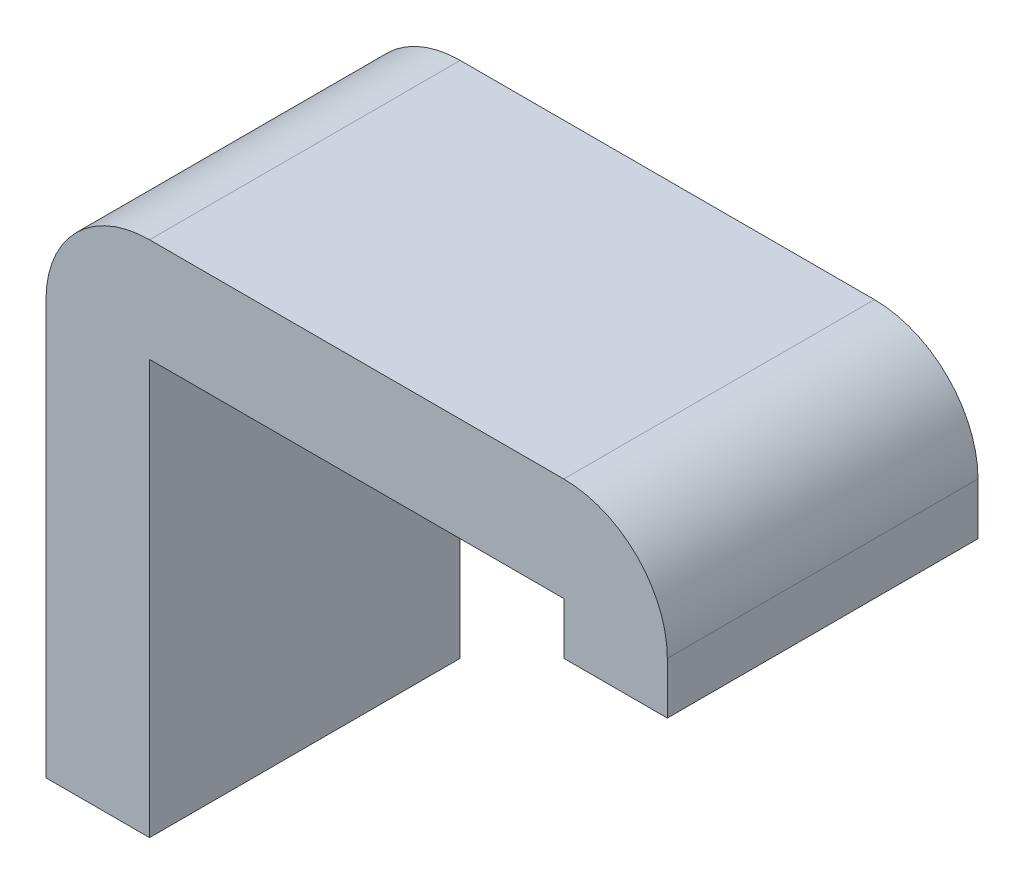
SolidWorks part; units mm, degrees
ref_plane "Plan de face" through (0, 0, 0) normal (0, 0, 1) x (1, 0, 0)
ref_plane "Plan de dessus" through (0, 0, 0) normal (0, 1, 0) x (1, 0, 0)
ref_plane "Plan de droite" through (0, 0, 0) normal (1, 0, 0) x (0, 0, -1)
sketch "Esquisse2" plane through (0, 0, 0) normal (0, 0, 1) x (1, 0, 0)
  line L0 (-35, 0) -> (35, 0)
  line L1 (35, 0) -> (35, -50)
  line L3 (-35, 0) -> (-35, -50)
  point P0 (0, 0)
  point P4 (0, 0)
  dimension "D1" = 50
  dimension "D2" = 70
  dimension "D3" = 50
sketch "Esquisse5" plane through (0, 0, 0) normal (0, 0, 1) x (1, 0, 0)
  line L0 (-20, 0) -> (20, 0)
  line L1 (-30, -10) -> (-30, -50)
  line L4 (30, -10) -> (30, -15)
  arc A0 (20, 0) -> (30, -10) centre (20, -10) cw
  arc A1 (-20, 0) -> (-30, -10) centre (-20, -10) ccw
  point P4 (0, 0)
  point P8 (30, 0)
  point P11 (-30, 0)
  point P12 (0, 0)
  point P13 (0, 0)
  dimension "D4" = 10
  dimension "D1" = 50
  dimension "D2" = 60
  dimension "D3" = 15
sketch "Esquisse7" plane through (0, 0, 0) normal (0, 1, 0) x (1, 0, 0)
  circle A0 centre (-20.3431, 18.4803) radius 44.0109
extrude "Extru.-Mince3" add sketch "Esquisse5" along normal blind 30 thin contours L4 A0 L0 A1 L1
sketch "Esquisse9" plane through (0, -50, 0) normal (0, -1, 0) x (1, 0, 0)
  line L0 (-28.3266, 28.158) -> (-21.9398, 28.158)
  line L1 (-21.9398, 28.158) -> (-21.9398, 2.3151)
  line L2 (-21.9398, 2.3151) -> (-28.3266, 2.3151)
  line L3 (-28.3266, 2.3151) -> (-28.3266, 28.158)
extrude "Enlèv. mat.-Extru.1" cut sketch "Esquisse9" against normal blind 40
sketch "Esquisse10" plane through (0, -15, 0) normal (0, -1, 0) x (1, 0, 0)
  line L0 (22.1763, 27.2709) -> (27.3804, 27.2709)
  line L1 (27.3804, 27.2709) -> (27.3804, 3.0839)
  line L2 (27.3804, 3.0839) -> (22.1763, 3.0839)
  line L3 (22.1763, 3.0839) -> (22.1763, 27.2709)
extrude "Enlèv. mat.-Extru.2" cut sketch "Esquisse10" against normal blind 10
